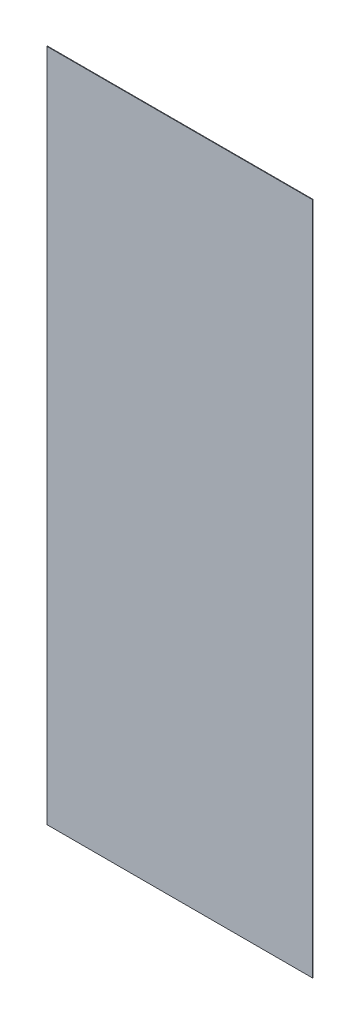
SolidWorks part; units mm, degrees
ref_plane "Front Plane" through (0, 0, 0) normal (0, 0, 1) x (1, 0, 0)
ref_plane "Top Plane" through (0, 0, 0) normal (0, 1, 0) x (1, 0, 0)
ref_plane "Right Plane" through (0, 0, 0) normal (1, 0, 0) x (0, 0, -1)
other "Configuration Table"
sketch "Sketch1" plane through (0, 0, 0) normal (0, 0, 1) x (1, 0, 0)
  line L1 (1.5, 200) -> (698.5, 200)
  line L2 (1.5, 200) -> (1.5, 1968.5)
  line L3 (1.5, 1968.5) -> (698.5, 1968.5)
  line L4 (698.5, 200) -> (698.5, 1968.5)
extrude "TOPPING_dis_arka_1" add sketch "Sketch1" against normal blind 1.5 from offset 818.5 separate body
